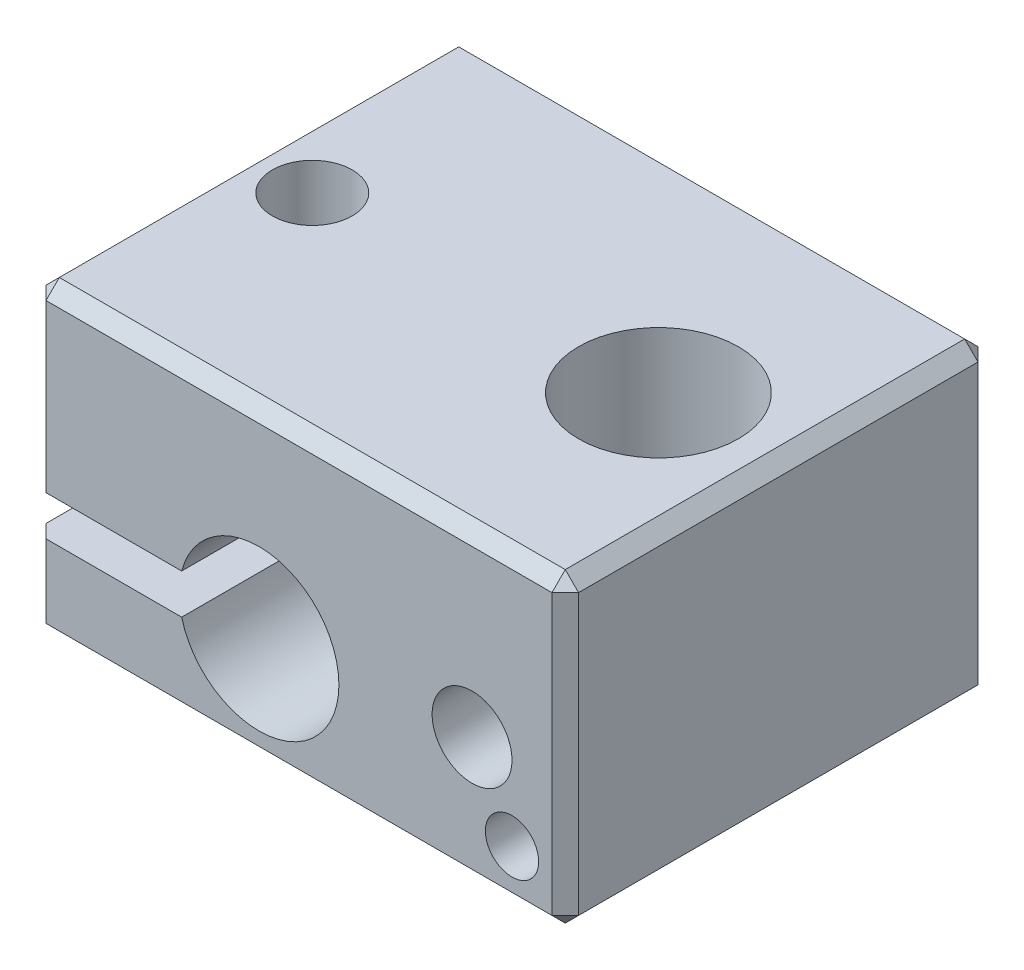
SolidWorks part; units mm, degrees
material "6061 Alloy"
ref_plane "Front Plane" through (0, 0, 0) normal (0, 0, 1) x (1, 0, 0)
ref_plane "Top Plane" through (0, 0, 0) normal (0, 1, 0) x (1, 0, 0)
ref_plane "Right Plane" through (0, 0, 0) normal (1, 0, 0) x (0, 0, -1)
sketch "Sketch1" plane through (0, 0, 0) normal (0, 1, 0) x (1, 0, 0)
  line L1 (-10, -8) -> (10, -8)
  line L2 (-10, -8) -> (-10, 8)
  line L3 (-10, 8) -> (10, 8)
  line L4 (10, -8) -> (10, 8)
  line L5 (-10, -8) -> (10, 8) construction
  line L6 (-10, 8) -> (10, -8) construction
  point P0 (0, 0)
  dimension "D1" = 20
  dimension "D2" = 16
extrude "Boss-Extrude1" add sketch "Sketch1" along normal blind 11.5
sketch "Sketch2" plane through (0, 0, 8) normal (0, 0, 1) x (1, 0, 0)
  line L0 (-1.5, 4) -> (-10, 4) construction
  line L1 (-10, 11.5) -> (-10, 0) construction
  line L2 (10, 11.5) -> (10, 0) construction
  line L3 (-10, 0) -> (10, 0) construction
  line L4 (-4.4047, 4.75) -> (-10, 4.75)
  line L5 (-10, 4.75) -> (-10, 4)
  line L6 (-10, 4) -> (-10, 3.25)
  line L7 (-10, 3.25) -> (-4.4047, 3.25)
  arc A0 (-4.4047, 3.25) -> (-4.4047, 4.75) centre (-1.5, 4) ccw
  dimension "D1" = 6
  dimension "D2" = 11.5
  dimension "D3" = 4
  dimension "D4" = 1.5
extrude "Cut-Extrude1" cut sketch "Sketch2" against normal through all
hole_wizard "M3 Tapped Hole1" positions "Sketch4" profile "Sketch3" tap size "M3" standard "ISO"
sketch "Sketch4" plane through (0, 0, 8) normal (0, 0, 1) x (1, 0, 0)
  line L0 (10, 11.5) -> (10, 0) construction
  line L1 (-10, 0) -> (10, 0) construction
  point P0 (6.5, 4.8)
  dimension "D1" = 3.5
  dimension "D2" = 4.8
sketch "Sketch3" plane through (6.5, 4.8, 8) normal (1, 0, 0) x (0, -1, 0)
  line L0 (0, 0) -> (0, 4.2511)
  line L1 (0, 4.2511) -> (1.25, 3.5)
  line L2 (1.25, 3.5) -> (1.25, 3)
  line L3 (1.25, 3) -> (1.5, 3)
  line L4 (1.5, 3) -> (1.5, 0)
  line L5 (1.5, 0) -> (0, 0)
  line L10 (0, 4.2511) -> (-1.25, 3.5) construction
  line L11 (0, -6.35) -> (0, 107.95) construction
  dimension "Tap Drill Dia." = 2.5
  dimension "Tap Drill Depth" = 3.5
  dimension "Thread Major Dia." = 3
  dimension "Thread Depth" = 3
  dimension "Drill Angle" = 118
hole_wizard "Hole1" positions "Sketch6" profile "Sketch5" legacy
sketch "Sketch6" plane through (0, 0, 8) normal (0, 0, 1) x (1, 0, 0)
  line L0 (10, 11.5) -> (10, 0) construction
  line L1 (-10, 0) -> (10, 0) construction
  point P0 (8, 2)
  dimension "D1" = 2
  dimension "D2" = 2
sketch "Sketch5" plane through (8, 2, 8) normal (1, 0, 0) x (0, -1, 0)
  line L0 (0, 0) -> (0, 4.5)
  line L1 (0, 4.5) -> (0.75, 4.5)
  line L2 (0.75, 4.5) -> (0.75, 2)
  line L3 (0.75, 2) -> (1, 2)
  line L4 (1, 2) -> (1, 0)
  line L5 (1, 0) -> (0, 0)
  line L6 (0, 110) -> (0, -10) construction
  dimension "Diameter" = 1.5
  dimension "Depth" = 4.5
  dimension "C-Bore Diameter" = 2
  dimension "C-Bore Depth" = 2
hole_wizard "M6 Tapped Hole1" positions "Sketch8" profile "Sketch9" tap size "M6" standard "ISO" end condition through all
sketch "Sketch8" plane through (0, 11.5, 0) normal (0, 1, 0) x (1, 0, 0)
  line L0 (-10, -8) -> (10, -8) construction
  line L1 (10, -8) -> (10, 8) construction
  point P0 (5.5, 0)
  dimension "D1" = 8
  dimension "D2" = 4.5
sketch "Sketch9" plane through (5.5, 11.5, 0) normal (1, 0, 0) x (0, 0, 1)
  line L0 (0, 0) -> (0, 11.5)
  line L1 (0, 11.5) -> (3, 11.5)
  line L2 (3, 11.5) -> (3, 0)
  line L5 (3, 0) -> (0, 0)
  line L11 (0, -6.35) -> (0, 107.95) construction
  dimension "Thread Major Dia." = 6
  dimension "Thru Tap Drill Depth" = 11.5
hole_wizard "M3 Tapped Hole2" positions "Sketch11" profile "Sketch10" tap size "M3" standard "ISO" end condition through all
sketch "Sketch11" plane through (0, 11.5, 0) normal (0, 1, 0) x (1, 0, 0)
  line L0 (-10, -8) -> (10, -8) construction
  line L2 (10, -8) -> (10, 8) construction
  point P0 (-7.5, 0)
  dimension "D1" = 8
  dimension "D2" = 17.5
sketch "Sketch10" plane through (-7.5, 11.5, 0) normal (1, 0, 0) x (0, 0, 1)
  line L0 (0, 0) -> (0, 11.5)
  line L1 (0, 11.5) -> (1.5, 11.5)
  line L2 (1.5, 11.5) -> (1.5, 0)
  line L5 (1.5, 0) -> (0, 0)
  line L11 (0, -6.35) -> (0, 107.95) construction
  dimension "Thread Major Dia." = 3
  dimension "Thru Tap Drill Depth" = 11.5
chamfer "Chamfer1" distance 0.5 14 edges at (10, 5.75, -8) (0, 0, -8) (10, 0, 0) (-10, 1.625, -8) (-10, 0, 0) (-10, 8.125, -8) (0, 11.5, -8) (10, 11.5, 0) (-10, 1.625, 8) (0, 0, 8) (10, 5.75, 8) (-10, 8.125, 8) (0, 11.5, 8) (-10, 11.5, 0)
